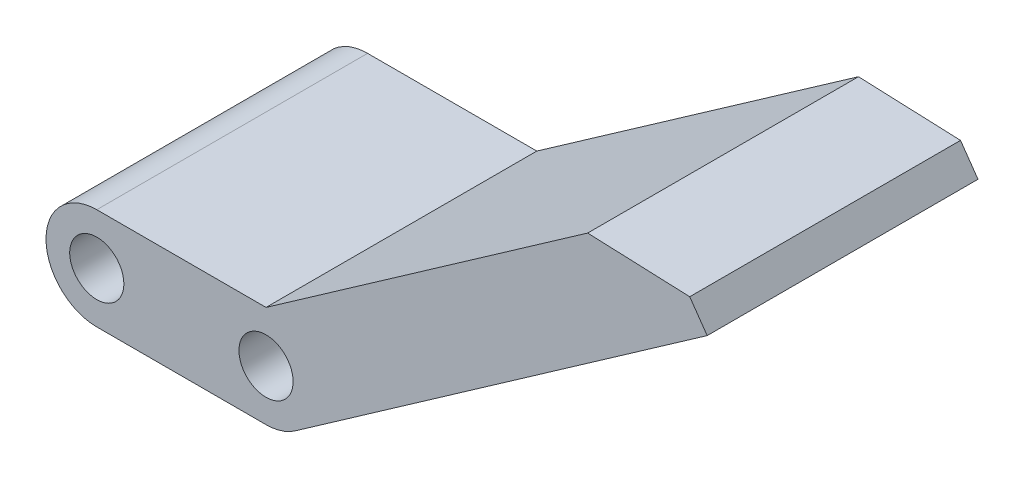
SolidWorks part; units mm, degrees
ref_plane "Front Plane" through (0, 0, 0) normal (0, 0, 1) x (1, 0, 0)
ref_plane "Top Plane" through (0, 0, 0) normal (0, 1, 0) x (1, 0, 0)
ref_plane "Right Plane" through (0, 0, 0) normal (1, 0, 0) x (0, 0, -1)
sketch "Sketch2" plane through (0, 0, 0) normal (0, 0, 1) x (1, 0, 0)
  line L0 (0, 0) -> (25, 0) construction
  line L1 (0, 7.5) -> (25, 7.5)
  line L2 (0, -7.5) -> (25, -7.5)
  line L4 (25, 7.5) -> (82.3406, 47.6504) construction
  line L5 (29.3018, -6.1436) -> (90.1663, 36.4741) construction
  line L6 (82.3406, 47.6504) -> (90.1663, 36.4741) construction
  line L7 (25, 7.5) -> (72.5108, 40.7674)
  line L8 (72.5108, 40.7674) -> (87.5852, 40.1603)
  line L9 (87.5852, 40.1603) -> (90.1663, 36.4741)
  line L10 (90.1663, 36.4741) -> (86.0706, 33.6063) construction
  line L12 (86.0706, 33.6063) -> (29.3018, -6.1436)
  line L23 (86.0706, 33.6063) -> (90.1663, 36.4741)
  arc A0 (0, 7.5) -> (0, -7.5) centre (0, 0) ccw
  arc A1 (25, -7.5) -> (25, 7.5) centre (25, 0) ccw
  circle A2 centre (0, 0) radius 4
  circle A3 centre (25, 0) radius 4
  point P3 (12.5, 0)
  point P12 (0, 0)
  point P14 (0, 0)
  point P15 (72.7309, 26.0649)
  point P19 (30, 7.5)
  dimension "D3" = 8
  dimension "D1" = 15
  dimension "D2" = 25
  dimension "D4" = 215
  dimension "D5" = 70
  dimension "D8" = 4.5
  dimension "D9" = 12
  dimension "D10" = 5
  dimension "D11" = 360
extrude "Boss-Extrude1" add sketch "Sketch2" along normal blind 40
